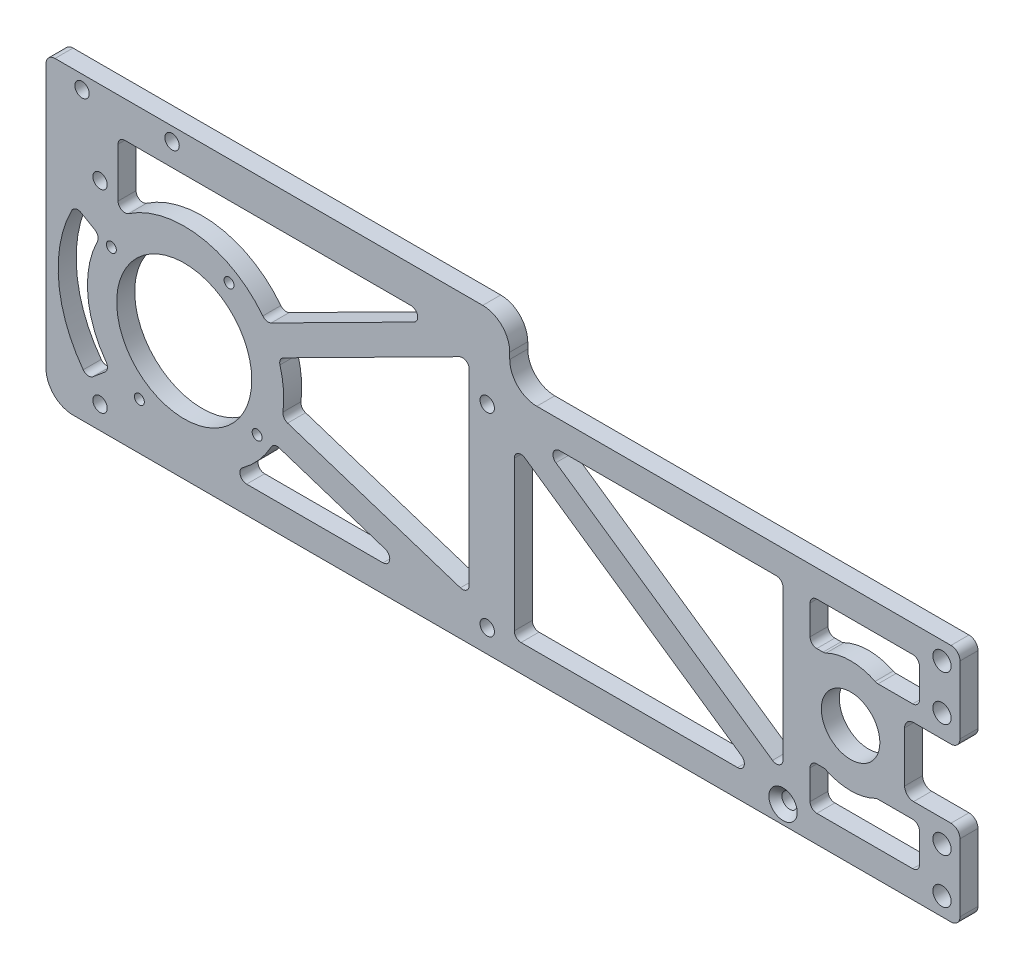
SolidWorks part; units mm, degrees
material "Thornel Mat VMA"
ref_plane "前视基准面" through (0, 0, 0) normal (0, 0, 1) x (1, 0, 0)
ref_plane "上视基准面" through (0, 0, 0) normal (0, 1, 0) x (1, 0, 0)
ref_plane "右视基准面" through (0, 0, 0) normal (1, 0, 0) x (0, 0, -1)
other "Configuration Table"
sketch "草图1" plane through (0, 0, 0) normal (0, 0, 1) x (1, 0, 0)
  line L1 (-175.7, 26.6) -> (24.3, 26.6)
  line L2 (-175.7, 26.6) -> (-175.7, -26.6)
  line L3 (-175.7, -26.6) -> (24.3, -26.6)
  line L4 (24.3, 26.6) -> (24.3, -26.6)
  circle A0 centre (0, 0) radius 6.5
  circle A1 centre (20.3, 22.6) radius 2.025
  circle A2 centre (20.3, 12.6) radius 2.025
  circle A3 centre (20.3, -12.6) radius 2.025
  circle A4 centre (20.3, -22.6) radius 2.025
  point P7 (24.3, 0)
  dimension "D1" = 4.05
  dimension "D7" = 13
  dimension "D2" = 24.3
  dimension "D3" = 4
  dimension "D4" = 10
  dimension "D5" = 10
  dimension "D6" = 25.2
  dimension "D8" = 12.6
  dimension "D9" = 4
  dimension "D10" = 200
extrude "凸台-拉伸1" add sketch "草图1" along normal mid plane 4
sketch "草图2" plane through (0, 0, 2) normal (0, 0, 1) x (1, 0, 0)
  circle A0 centre (-148, 0) radius 20
  dimension "D1" = 40
  dimension "D2" = 148
extrude "切除-拉伸1" cut sketch "草图2" against normal blind 5
sketch "草图3" plane through (0, 0, 2) normal (0, 0, 1) x (1, 0, 0)
  line L1 (-136.212, -26.6) -> (-139.2728, -12.1998)
  line L3 (-161.9638, -5.4785) -> (-175.7, -19.2147)
  line L4 (-175.7, -26.6) -> (24.3, -26.6) construction
  line L5 (-175.7, 26.6) -> (-175.7, -26.6) construction
  line L6 (-175.7, -26.6) -> (-136.212, -26.6)
  line L7 (-175.7, -19.2147) -> (-175.7, -26.6)
  arc A0 (-161.9638, -5.4785) -> (-139.2728, -12.1998) centre (-148, 0) ccw
  dimension "D1" = 30
extrude "切除-拉伸2" cut sketch "草图3" against normal blind 10
sketch "草图4" plane through (0, 0, 2) normal (0, 0, 1) x (1, 0, 0)
  circle A6 centre (-148, 0) radius 24.5 construction
  circle A7 centre (-141, 23.4787) radius 1.1
  circle A8 centre (-131.1668, -17.8015) radius 1.1
  circle A9 centre (-171.8332, -5.6772) radius 1.1
  circle A10 centre (-148, 0) radius 30 construction
  point P11 (-148, 0)
  dimension "D1" = 2.2
  dimension "D2" = 49
  dimension "D4" = 60
  dimension "D3" = 7
extrude "切除-拉伸3" cut sketch "草图4" against normal blind 10
sketch "草图5" plane through (0, 0, 2) normal (0, 0, 1) x (1, 0, 0)
  line L0 (-170.7, 37) -> (-150.7, 37) construction
  line L1 (-175.7, 26.6) -> (-75.7, 26.6)
  line L2 (-175.7, 26.6) -> (-175.7, 40)
  line L3 (-175.7, 40) -> (-75.7, 40)
  line L4 (-75.7, 26.6) -> (-75.7, 40)
  circle A0 centre (-148, 0) radius 28 construction
  circle A1 centre (-170.7, 37) radius 1.6
  circle A2 centre (-150.7, 37) radius 1.6
  dimension "D1" = 56
  dimension "D5" = 3.2
  dimension "D2" = 12
  dimension "D3" = 100
  dimension "D4" = 3
  dimension "D6" = 20
  dimension "D7" = 5
extrude "凸台-拉伸2" add sketch "草图5" against normal blind 4
sketch "草图6" plane through (0, 0, 2) normal (0, 0, 1) x (1, 0, 0)
  line L0 (-175.7, 40) -> (-178.7, 40)
  line L1 (-178.7, 40) -> (-178.7, -22.2147)
  line L2 (-178.7, -22.2147) -> (-175.7, -19.2147)
  line L3 (-175.7, -19.2147) -> (-175.7, 40)
  line L4 (-165.7334, -9.2481) -> (-175.7, -19.2147) construction
  dimension "D1" = 3
extrude "凸台-拉伸3" add sketch "草图6" against normal blind 4
sketch "草图7" plane through (0, 0, 2) normal (0, 0, 1) x (1, 0, 0)
  line L0 (-136.212, -26.6) -> (-178.7, -26.6)
  line L1 (-178.7, -26.6) -> (-178.7, -22.2147)
  line L2 (-136.212, -26.6) -> (-138.1644, -17.4144) construction
  line L3 (-165.7334, -9.2481) -> (-178.7, -22.2147) construction
  line L4 (-136.212, -26.6) -> (-138.1644, -17.4144)
  line L5 (-165.7334, -9.2481) -> (-178.7, -22.2147)
  circle A0 centre (-141, 23.4787) radius 1.1 construction
  circle A1 centre (-171.8332, -5.6772) radius 1.1 construction
  circle A2 centre (-131.1668, -17.8015) radius 1.1 construction
  arc A3 (-138.1644, -17.4144) -> (-165.7334, -9.2481) centre (-148, 0) ccw construction
  circle A4 centre (-141, 23.4787) radius 1.1
  circle A5 centre (-171.8332, -5.6772) radius 1.1
  circle A6 centre (-131.1668, -17.8015) radius 1.1
  arc A7 (-138.1644, -17.4144) -> (-165.7334, -9.2481) centre (-148, 0) ccw
  circle A8 centre (-148, 0) radius 15
  circle A9 centre (-148, 0) radius 19 construction
  dimension "D1" = 30
  dimension "D2" = 38
extrude "凸台-拉伸4" add sketch "草图7" against normal blind 4
sketch "草图9" plane through (0, 0, 2) normal (0, 0, 1) x (1, 0, 0)
  circle A0 centre (-138.0438, 16.1825) radius 1.1
  circle A1 centre (-164.1825, 9.9562) radius 1.1
  circle A2 centre (-157.9562, -16.1825) radius 1.1
  circle A3 centre (-131.8175, -9.9562) radius 1.1
  dimension "D1" = 2.2
extrude "切除-拉伸4" cut sketch "草图9" against normal blind 10
sketch "草图11" plane through (0, 0, 2) normal (0, 0, 1) x (1, 0, 0)
  line L0 (-166.7, 21.5) -> (-80.7, 21.5) construction
  line L1 (-178.7, 40) -> (-178.7, -26.6) construction
  line L2 (-75.7, 40) -> (-178.7, 40) construction
  circle A0 centre (-166.7, 21.5) radius 1.6
  circle A1 centre (-80.7, 21.5) radius 1.6
  circle A2 centre (-166.7, -21.5) radius 1.6
  circle A3 centre (-80.7, -21.5) radius 1.6
  dimension "D4" = 3.2
  dimension "D1" = 86
  dimension "D2" = 12
  dimension "D3" = 18.5
  dimension "D5" = 43
extrude "切除-拉伸6" cut sketch "草图11" against normal blind 4
fillet "圆角1" radius 6 3 edges at (-75.7, 26.6, 0) (-75.7, 40, 0) (-178.7, -26.6, 0)
sketch "草图17" plane through (0, 0, 2) normal (0, 0, 1) x (1, 0, 0)
  line L0 (24.3, -26.6) -> (24.3, 26.6) construction
  line L1 (24.3, -7.6) -> (12, -7.6)
  line L2 (24.3, -7.6) -> (24.3, 7.6)
  line L3 (24.3, 7.6) -> (12, 7.6)
  line L4 (12, -7.6) -> (12, 7.6)
  line L5 (24.3, 26.6) -> (-69.7, 26.6) construction
  line L6 (15.3, 11.1) -> (-9, 11.1)
  line L7 (15.3, 11.1) -> (15.3, 20.6)
  line L8 (15.3, 20.6) -> (-9, 20.6)
  line L9 (-9, 11.1) -> (-9, 20.6)
  line L10 (0, 0) -> (-12.5, 0) construction
  line L11 (15.3, -20.6) -> (-9, -20.6)
  line L12 (-9, -11.1) -> (-9, -20.6)
  line L13 (15.3, -11.1) -> (-9, -11.1)
  line L14 (15.3, -11.1) -> (15.3, -20.6)
  circle A0 centre (0, 0) radius 12.5
  circle A1 centre (20.3, -12.6) radius 2.025 construction
  circle A2 centre (20.3, 22.6) radius 2.025 construction
  point P9 (24.3, 0)
  point P16 (18.15, 7.6)
  line M25 (24.3, -26.6) -> (24.3, 26.6)
  dimension "D3" = 25
  dimension "D1" = 12
  dimension "D2" = 5
  dimension "D4" = 3.5
  dimension "D5" = 5
  dimension "D6" = 6
  dimension "D7" = 3.5
extrude "切除-拉伸9" cut sketch "草图17" against normal blind 4 contours A0 L13 L12 L11 L14 | A0 L4 L1 L3 M25 | A0 L6 L7 L8 L9 | L4 A0
sketch "草图18" plane through (0, 0, 2) normal (0, 0, 1) x (1, 0, 0)
  line L0 (15.3, -20.6) -> (-9, -20.6) construction
  line L1 (-74.7, 20.6) -> (-15, 20.6)
  line L2 (-74.7, 20.6) -> (-74.7, -20.6)
  line L3 (-74.7, -20.6) -> (-15, -20.6)
  line L4 (-15, 20.6) -> (-15, -20.6)
  line L5 (15.3, 20.6) -> (-9, 20.6) construction
  line L6 (-9, -11.1) -> (-9, -20.6) construction
  line L7 (-15, -20.6) -> (-74.7, 20.6) construction
  line L8 (-20.2818, -20.6) -> (-74.7, 16.955)
  line L9 (-69.4182, 20.6) -> (-15, -16.955)
  circle A0 centre (-80.7, -21.5) radius 1.6 construction
  dimension "D1" = 6
  dimension "D2" = 6
  dimension "D3" = 6
extrude "切除-拉伸10" cut sketch "草图18" against normal blind 4 contours L3 L8 L2 | L1 L9 L4
sketch "草图19" plane through (0, 0, 2) normal (0, 0, 1) x (1, 0, 0)
  line L0 (-74.7, -20.6) -> (-165.3771, -20.6)
  line L1 (-84.7, -20.6) -> (-84.7, 32)
  line L2 (-84.7, 32) -> (-162.7, 32)
  line L3 (-162.7, 32) -> (-162.7, 16.5021)
  line L4 (-74.7, 16.955) -> (-74.7, -20.6) construction
  line L5 (-148, 0) -> (-69.0222, 0) construction
  line L6 (-84.7, 32) -> (-148, 0) construction
  line L7 (-84.7, -20.6) -> (-148, 0) construction
  line L8 (-127.1061, 7.2009) -> (-84.7, 28.6384)
  line L9 (-129.813, 12.5556) -> (-91.3496, 32)
  line L10 (-94.3943, -20.6) -> (-128.1077, -9.6285)
  line L11 (-84.7, -17.4451) -> (-126.251, -3.923)
  circle A0 centre (-148, 0) radius 22.1
  circle A1 centre (-131.8175, -9.9562) radius 1.1 construction
  circle A2 centre (-166.7, -21.5) radius 1.6 construction
  circle A3 centre (-166.7, 21.5) radius 1.6 construction
  circle A4 centre (-150.7, 37) radius 1.6 construction
  dimension "D1" = 2
  dimension "D2" = 4
  dimension "D3" = 5
  dimension "D4" = 10
  dimension "D5" = 6
  dimension "D6" = 6
extrude "切除-拉伸11" cut sketch "草图19" against normal blind 4 contours A0 L0 L10 | A0 L11 L1 L8 | A0 L9 L2 L3
fillet "圆角2" radius 1.5 29 edges at (-127.1061, 7.2009, 0) (-84.7, 28.6384, 0) (-84.7, -17.4451, 0) (-126.251, -3.923, 0) (-128.1077, -9.6285, 0) (-94.3943, -20.6, 0) (-139.9969, -20.6, 0) (-5.748, -11.1, 0) (5.748, -11.1, 0) (15.3, -11.1, 0) (15.3, -20.6, 0) (-9, -20.6, 0) (-9, -11.1, 0) (5.748, 11.1, 0) (-5.748, 11.1, 0) (-9, 11.1, 0) (-9, 20.6, 0) (15.3, 20.6, 0) (15.3, 11.1, 0) (-20.2818, -20.6, 0) (-74.7, -20.6, 0) (-15, 20.6, 0) (-15, -16.955, 0) (-69.4182, 20.6, 0) (-162.7, 16.5021, 0) (-162.7, 32, 0) (-91.3496, 32, 0) (-129.813, 12.5556, 0) (-74.7, 16.955, 0)
sketch "草图20" plane through (0, 0, 2) normal (0, 0, 1) x (1, 0, 0)
  line L0 (-148, 0) -> (-172.2487, 14)
  line L1 (-148, 0) -> (-177.2337, -24.53)
  line L2 (-148, 0) -> (-178.7, 0) construction
  line L3 (-178.7, 40) -> (-178.7, -20.6) construction
  circle A0 centre (-148, 0) radius 21.5
  circle A1 centre (-148, 0) radius 28
  arc A2 (-178.7, -20.6) -> (-172.7, -26.6) centre (-172.7, -20.6) ccw construction
  dimension "D1" = 43
  dimension "D2" = 56
  dimension "D3" = 30
  dimension "D4" = 40
extrude "切除-拉伸12" cut sketch "草图20" against normal blind 4 contours A0 L2 A1 L1 | L2 A0 L0 A1
fillet "圆角3" radius 1.5 4 edges at (-164.47, -13.8199, 0) (-169.4492, -17.9981, 0) (-166.6195, 10.75, 0) (-172.2487, 14, 0)
sketch "草图21" plane through (0, 0, 2) normal (0, 0, 1) x (1, 0, 0)
  line L0 (-172.7, -26.6) -> (24.3, -26.6) construction
  circle A0 centre (-15, -22.6) radius 1.55
  dimension "D1" = 3.1
  dimension "D3" = 4
  dimension "D2" = 15
extrude "切除-拉伸13" cut sketch "草图21" against normal blind 10
fillet "圆角4" radius 2 7 edges at (24.3, 26.6, 0) (-178.7, 40, 0) (24.3, -26.6, 0) (24.3, -7.6, 0) (12, -7.6, 0) (12, 7.6, 0) (24.3, 7.6, 0)
sketch "草图22" plane through (0, 0, 2) normal (0, 0, 1) x (1, 0, 0)
  point P0 (-15, -22.6)
hole_wizard "M3 锥坑平头螺钉的锥形沉头孔1" positions "草图22" profile "草图23" countersink size "M3" standard "ISO" end condition through all
sketch "草图23" plane through (-15, -22.6, 2) normal (1, 0, 0) x (0, -1, 0)
  line L0 (0, 0) -> (0, 4)
  line L1 (0, 4) -> (1.7, 4)
  line L2 (1.7, 4) -> (1.7, 1.45)
  line L3 (1.7, 1.45) -> (3.15, 0)
  line L5 (3.15, 0) -> (0, 0)
  line L6 (-1.7, 1.45) -> (-3.15, 0) construction
  line L11 (0, -6.35) -> (0, 107.95) construction
  dimension "通孔孔直径" = 3.4
  dimension "通孔孔深度" = 4
  dimension "近端锥形沉头孔直径" = 6.3
  dimension "近端锥形沉头孔角度" = 90
